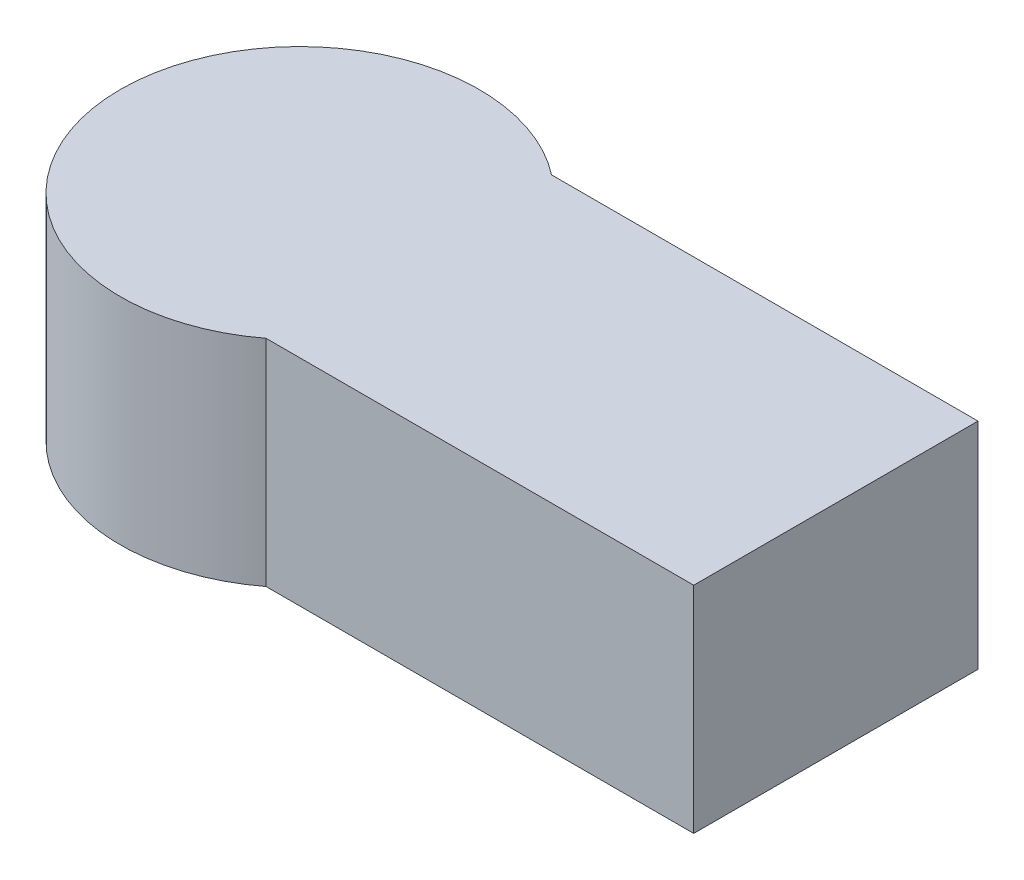
SolidWorks part; units mm, degrees
ref_plane "Alzado" through (0, 0, 0) normal (0, 0, 1) x (1, 0, 0)
ref_plane "Planta" through (0, 0, 0) normal (0, 1, 0) x (1, 0, 0)
ref_plane "Vista lateral" through (0, 0, 0) normal (1, 0, 0) x (0, 0, -1)
sketch "Croquis2" plane through (0, 0, 0) normal (0, 1, 0) x (1, 0, 0)
  line L1 (31, 39.8654) -> (151, 39.8654)
  line L3 (30.6507, -40.1346) -> (151, -40.1346)
  line L4 (151, 39.8654) -> (151, -40.1346)
  line L5 (150, 38.8654) -> (26.1607, 38.8654)
  line L6 (150, 38.8654) -> (150, -39.1346)
  line L7 (150, -39.1346) -> (26.1607, -39.1346)
  line L8 (26.1607, 38.8654) -> (26.1607, -39.1346)
  arc A0 (31, 39.8654) -> (30.6507, -40.1346) centre (0, 0) ccw
  circle A1 centre (0, 0) radius 49.5
  dimension "D1" = 101
  dimension "D4" = 151
  dimension "D5" = 1
  dimension "D8" = 1
  dimension "D9" = 10.6346
  dimension "D2" = 120
  dimension "D3" = 80
  dimension "D6" = 1
  dimension "D7" = 1
extrude "Saliente-Extruir1" add sketch "Croquis2" along normal blind 65 contours L6 L5 L8 L7 | A1 | L1 L4 L3 A0
sketch "Croquis3" plane through (0, 65, 0) normal (0, 1, 0) x (1, 0, 0)
  line L0 (151, 39.8654) -> (151, -40.1346)
  line L1 (151, -40.1346) -> (30.6507, -40.1346)
  line L2 (151, 39.8654) -> (31, 39.8654)
  arc A0 (31, 39.8654) -> (30.6507, -40.1346) centre (0, 0) ccw
extrude "Saliente-Extruir2" add sketch "Croquis3" along normal blind 2.5
sketch "Croquis4" plane through (151, 0, 0) normal (1, 0, 0) x (0, 0, -1)
  line L1 (-50.5, 67.5) -> (50.5, 67.5)
  line L2 (-50.5, 67.5) -> (-50.5, 57.5)
  line L3 (-50.5, 57.5) -> (50.5, 57.5)
  line L4 (50.5, 67.5) -> (50.5, 57.5)
  dimension "D1" = 10
extrude "Cortar-Extruir1" cut sketch "Croquis4" against normal blind 250
sketch "Croquis5" plane through (0, 57.5, 0) normal (0, 1, 0) x (1, 0, 0)
  line L0 (151, 39.8654) -> (31, 39.8654)
  line L1 (151, 39.8654) -> (151, -40.1346)
  line L2 (151, -40.1346) -> (30.6507, -40.1346)
  arc A0 (31, 39.8654) -> (30.6507, -40.1346) centre (0, 0) ccw
extrude "Saliente-Extruir3" add sketch "Croquis5" along normal blind 3
